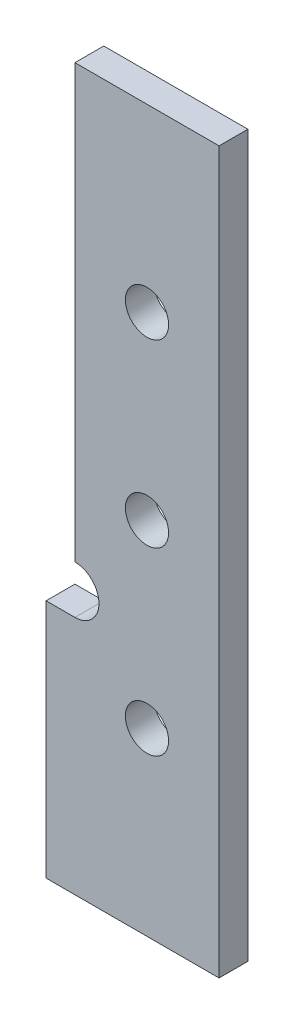
SolidWorks part; units mm, degrees
ref_plane "Front Plane" through (0, 0, 0) normal (0, 0, 1) x (1, 0, 0)
ref_plane "Top Plane" through (0, 0, 0) normal (0, 1, 0) x (1, 0, 0)
ref_plane "Right Plane" through (0, 0, 0) normal (1, 0, 0) x (0, 0, -1)
sketch "Sketch1" plane through (0, 0, 0) normal (0, 0, 1) x (1, 0, 0)
  line L0 (0, 100) -> (30, 100)
  line L1 (30, 100) -> (30, -50)
  line L2 (30, -50) -> (-6, -50)
  line L3 (-6, -50) -> (-6, 0)
  line L4 (-6, 0) -> (0, 0)
  line L5 (0, 0) -> (0, 100)
  point P5 (0, 0)
  dimension "D1" = 6
  dimension "D2" = 100
  dimension "D3" = 50
  dimension "D4" = 30
extrude "Boss-Extrude1" add sketch "Sketch1" along normal blind 6
hole_wizard "M8 Clearance Hole1" positions "Sketch3" profile "Sketch4" hole size "M8" standard "ANSI Metric" end condition through all
sketch "Sketch3" plane through (0, 0, 6) normal (0, 0, 1) x (1, 0, 0)
  line L0 (30, 100) -> (0, 100) construction
  line L1 (15, 25) -> (15, 62.5) construction
  line L2 (15, 62.5) -> (15, 100) construction
  line L4 (15, 25) -> (15, -12.5) construction
  line L5 (15, -12.5) -> (15, -50) construction
  line L6 (-6, -50) -> (30, -50) construction
  point P0 (15, 62.5)
  point P2 (15, 25)
  point P4 (15, -12.5)
  point P9 (15, 100)
sketch "Sketch4" plane through (15, 62.5, 6) normal (1, 0, 0) x (0, -1, 0)
  line L0 (0, 0) -> (0, 6)
  line L1 (0, 6) -> (4.5, 6)
  line L2 (4.5, 6) -> (4.5, 0)
  line L5 (4.5, 0) -> (0, 0)
  line L11 (0, -6.35) -> (0, 107.95) construction
  dimension "Thru Hole Dia." = 9
  dimension "Thru Hole Depth" = 6
sketch "Sketch5" plane through (0, 0, 0) normal (0, 0, -1) x (-1, 0, 0)
  line L0 (0, 100) -> (0, 0) construction
  circle A0 centre (0, 5) radius 5
  dimension "D1" = 10
extrude "Cut-Extrude1" cut sketch "Sketch5" against normal through all
